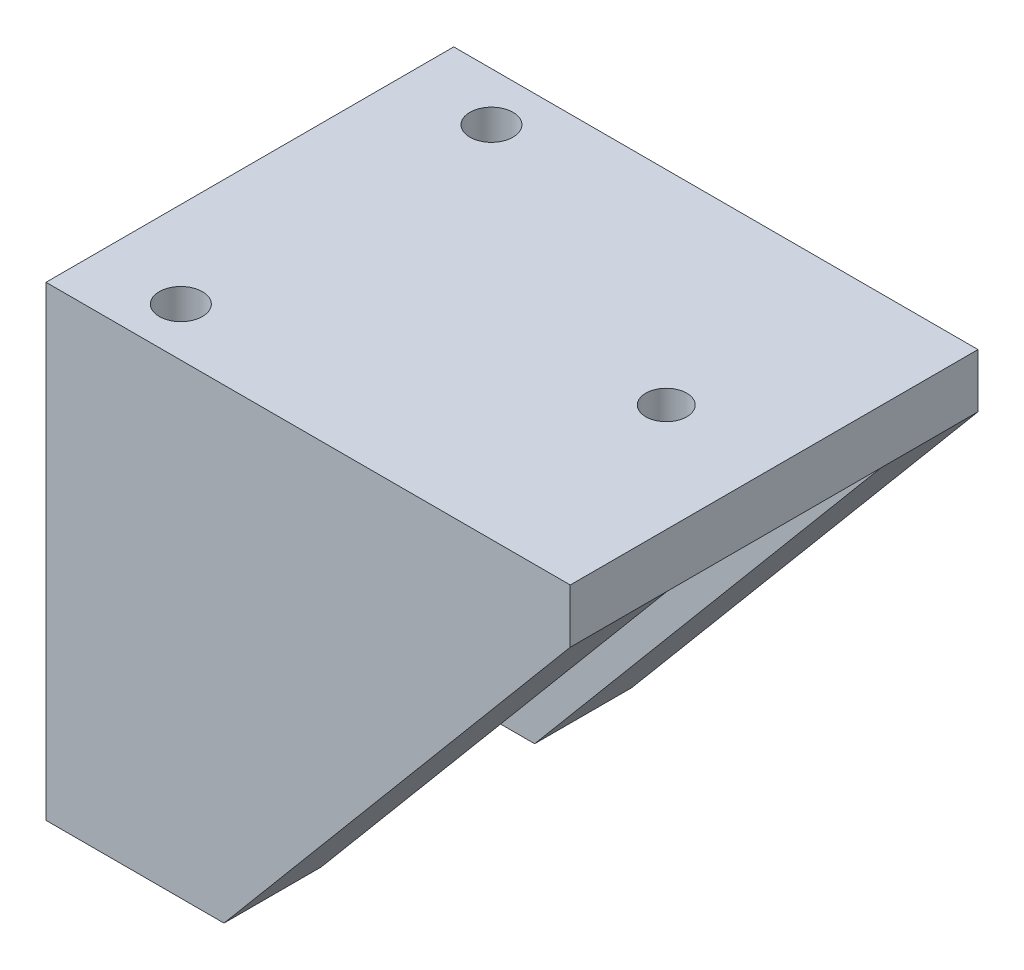
SolidWorks part; units mm, degrees
ref_plane "前基準面" through (0, 0, 0) normal (0, 0, 1) x (1, 0, 0)
ref_plane "上基準面" through (0, 0, 0) normal (0, 1, 0) x (1, 0, 0)
ref_plane "右基準面" through (0, 0, 0) normal (1, 0, 0) x (0, 0, -1)
sketch "草圖1" plane through (0, 0, 0) normal (0, 0, 1) x (1, 0, 0)
  line L0 (-40.6731, 29.7) -> (-40.6731, 2.8)
  line L1 (-0.0731, 34.7) -> (-0.0731, 29.7)
  line L2 (-48.6731, -8.5) -> (-40.6731, -8.5)
  line L3 (-40.6731, -8.5) -> (-40.6731, -3.2)
  line L4 (-48.6731, -8.5) -> (-48.6731, 0)
  line L6 (-48.6731, 0) -> (-40.6731, 0)
  line L7 (-48.6731, 2.8) -> (-40.6731, 2.8)
  line L8 (-40.6731, 0) -> (-40.6731, -3.2)
  line L11 (-48.6731, 2.8) -> (-48.6731, 34.7)
  line L12 (-41.6731, 34.7) -> (-48.6731, 34.7)
  line L17 (-41.6731, 34.7) -> (-0.0731, 34.7)
  line L19 (-40.6731, 29.7) -> (-0.0731, 29.7)
  dimension "D1" = 5
  dimension "D2" = 43.2
  dimension "D3" = 8
  dimension "D4" = 31.9
  dimension "D6" = 2.8
  dimension "D7" = 40.6
extrude "填料-伸長1" add sketch "草圖1" along normal blind 19.8
sketch "草圖2" plane through (-48.6731, 0, 0) normal (-1, 0, 0) x (0, 0, 1)
  line L0 (19.8, 0) -> (0, 0) construction
  line L1 (9.4, 0) -> (10.4, 0)
  line L2 (9.4, 0) -> (9.4, -0.8)
  line L3 (9.4, -0.8) -> (10.4, -0.8)
  line L4 (10.4, 0) -> (10.4, -0.8)
  dimension "D1" = 1
  dimension "D3" = 0.8
extrude "除料-伸長1" cut sketch "草圖2" against normal up to surface (8 mm away) up to face at (-40.6731, -4.25, 9.9)
sketch "草圖3" plane through (0, 0, 19.8) normal (0, 0, 1) x (1, 0, 0)
  line L0 (-48.6731, -8.5) -> (-32.1731, -8.5)
  line L1 (-0.0731, 34.7) -> (-0.0731, 29.7)
  line L2 (-0.0731, 29.7) -> (-32.1731, -8.5)
  line L4 (-0.0731, 34.7) -> (-48.6731, 34.7)
  line L6 (-48.6731, 34.7) -> (-48.6731, -8.5)
  dimension "D1" = 16.5
extrude "填料-伸長2" add sketch "草圖3" along normal blind 9
sketch "草圖4" plane through (0, 0, 0) normal (0, 0, -1) x (-1, 0, 0)
  line L0 (48.6731, -8.5) -> (48.6731, 34.7)
  line L1 (48.6731, 34.7) -> (0.0731, 34.7)
  line L2 (0.0731, 34.7) -> (0.0731, 29.7)
  line L3 (0.0731, 29.7) -> (32.1731, -8.5)
  line L4 (32.1731, -8.5) -> (48.6731, -8.5)
  dimension "D1" = 16.5
extrude "填料-伸長3" add sketch "草圖4" along normal blind 9
sketch "草圖5" plane through (0, 34.7, 0) normal (0, 1, 0) x (1, 0, 0)
  line L0 (-0.0731, -28.8) -> (-0.0731, 9) construction
  line L1 (-0.0731, -28.8) -> (-0.0731, 9) construction
  circle A0 centre (-10.0731, -9.9) radius 1.9
  point P6 (-0.0731, -9.9)
  dimension "D1" = 3.8
  dimension "D2" = 10
  dimension "D3" = 0
extrude "除料-伸長2" cut sketch "草圖5" against normal up to next
sketch "草圖8" plane through (-48.6731, 0, 0) normal (-1, 0, 0) x (0, 0, 1)
  line L0 (28.8, -8.5) -> (-9, -8.5) construction
  line L1 (0, 0) -> (19.8, 0)
  line L2 (0, 0) -> (0, -8.5)
  line L3 (0, -8.5) -> (19.8, -8.5)
  line L4 (19.8, 0) -> (19.8, -8.5)
  dimension "D1" = 19.8
extrude "除料-伸長5" cut sketch "草圖8" against normal up to surface (8 mm away) up to face at (-40.6731, 16.25, 9.9)
sketch "草圖9" plane through (0, 2.8, 0) normal (0, -1, 0) x (1, 0, 0)
  line L0 (-40.6731, 19.8) -> (-40.6731, 0) construction
  line L1 (-40.6731, 19.8) -> (-40.6731, 0) construction
  circle A0 centre (-45.2731, 14.9) radius 2.15
  circle A1 centre (-45.2731, 4.9) radius 2.15
  point P8 (-40.6731, 9.9)
  dimension "D1" = 4.6
  dimension "D2" = 4.3
  dimension "D3" = 4.3
  dimension "D4" = 4.6
  dimension "D5" = 5
  dimension "D6" = 10
extrude "填料-伸長4" add sketch "草圖9" along normal blind 5
sketch "草圖10" plane through (0, -8.5, 0) normal (0, -1, 0) x (-1, 0, 0)
  line L2 (40.6731, -19.8) -> (40.6731, 0) construction
  line L3 (48.6731, -28.8) -> (48.6731, -19.8) construction
  line L5 (48.6731, 0) -> (48.6731, 9) construction
  circle A0 centre (40.6731, -24.3) radius 2
  circle A1 centre (40.6731, 4.4958) radius 2
  point P6 (48.6731, -24.3)
  point P11 (40.6731, -9.9)
  dimension "D1" = 4
  dimension "D2" = 4
  dimension "D3" = 8
  dimension "D4" = 8
  dimension "D5" = 14.4
  dimension "D6" = 28.7958
extrude "除料-伸長6" cut sketch "草圖10" against normal up to next
